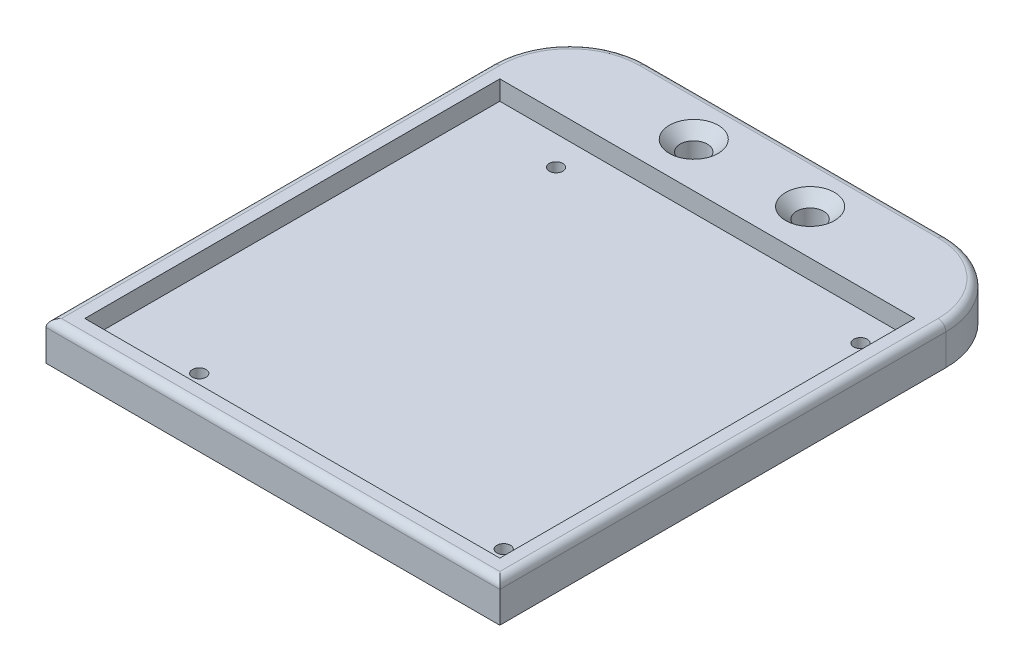
SolidWorks part; units mm, degrees
ref_plane "Front Plane" through (0, 0, 0) normal (0, 0, 1) x (1, 0, 0)
ref_plane "Top Plane" through (0, 0, 0) normal (0, 1, 0) x (1, 0, 0)
ref_plane "Right Plane" through (0, 0, 0) normal (1, 0, 0) x (0, 0, -1)
sketch "Sketch2" plane through (0, 0, 0) normal (0, 1, 0) x (1, 0, 0)
  line L1 (-58.5, 67.5) -> (58.5, 67.5)
  line L2 (-58.5, 67.5) -> (-58.5, -67.5)
  line L3 (-58.5, -67.5) -> (58.5, -67.5)
  line L4 (58.5, 67.5) -> (58.5, -67.5)
  line L5 (-58.5, 67.5) -> (58.5, -67.5) construction
  line L6 (-58.5, -67.5) -> (58.5, 67.5) construction
  point P0 (0, 0)
  dimension "D1" = 117
  dimension "D2" = 135
extrude "Boss-Extrude1" add sketch "Sketch2" along normal blind 10
sketch "Sketch4" plane through (0, 10, 0) normal (0, 1, 0) x (1, 0, 0)
  line L1 (-53.5, 44.5) -> (53.5, 44.5)
  line L2 (-53.5, 44.5) -> (-53.5, -62.5)
  line L3 (-53.5, -62.5) -> (53.5, -62.5)
  line L4 (53.5, 44.5) -> (53.5, -62.5)
  line L5 (-53.5, 44.5) -> (53.5, -62.5) construction
  line L6 (-53.5, -62.5) -> (53.5, 44.5) construction
  point P0 (0, -9)
  point P5 (0, 0)
  dimension "D1" = 107
  dimension "D2" = 107
  dimension "D3" = 5
extrude "Cut-Extrude1" cut sketch "Sketch4" against normal blind 5
sketch "Sketch3" plane through (0, 5, 0) normal (0, 1, 0) x (1, 0, 0)
  line L0 (53.5, -62.5) -> (53.5, 44.5) construction
  line L1 (-31.5, 37) -> (47, 37) construction
  line L2 (-31.5, 37) -> (-31.5, -55) construction
  line L3 (-31.5, -55) -> (47, -55) construction
  line L4 (47, 37) -> (47, -55) construction
  line L5 (-31.5, 37) -> (47, -55) construction
  line L6 (-31.5, -55) -> (47, 37) construction
  line L7 (53.5, 44.5) -> (-53.5, 44.5) construction
  circle A0 centre (-31.5, 37) radius 1.75
  circle A1 centre (47, 37) radius 1.75
  circle A2 centre (47, -55) radius 1.75
  circle A3 centre (-31.5, -55) radius 1.75
  point P0 (7.75, -9)
  point P9 (6.6065, -5.6847)
  dimension "D3" = 3.5
  dimension "D4" = 3.5
  dimension "D5" = 3.5
  dimension "D6" = 3.5
  dimension "D1" = 78.5
  dimension "D2" = 92
  dimension "D7" = 6.5
  dimension "D8" = 7.5
extrude "Cut-Extrude2" cut sketch "Sketch3" against normal through all
sketch "Sketch5" plane through (0, 10, 0) normal (0, 1, 0) x (1, 0, 0)
  line L0 (15, 56) -> (-15, 56) construction
  line L1 (53.5, 44.5) -> (-53.5, 44.5) construction
  point P2 (0, 56)
  dimension "D1" = 30
  dimension "D2" = 11.5
hole_wizard "CSK for M6 Flat Head Machine Screw1" positions "Sketch6" profile "Sketch7" countersink size "M6" standard "ANSI Metric" end condition through all
sketch "Sketch6" plane through (0, 10, 0) normal (0, 1, 0) x (1, 0, 0)
  point P0 (-15, 56)
  point P3 (15, 56)
sketch "Sketch7" plane through (-15, 10, -56) normal (1, 0, 0) x (0, 0, 1)
  line L0 (0, 0) -> (0, 10)
  line L1 (0, 10) -> (3.5, 10)
  line L2 (3.5, 10) -> (3.5, 2.8)
  line L3 (3.5, 2.8) -> (6.3, 0)
  line L5 (6.3, 0) -> (0, 0)
  line L6 (-3.5, 2.8) -> (-6.3, 0) construction
  line L11 (0, -6.35) -> (0, 107.95) construction
  dimension "Thru Hole Dia." = 7
  dimension "Thru Hole Depth" = 10
  dimension "Near C'Sink Dia." = 12.6
  dimension "Near C'Sink Angle" = 90
fillet "Fillet1" radius 20 2 edges at (58.5, 5, -67.5) (-58.5, 5, -67.5)
fillet "Fillet2" radius 2 6 edges at (58.5, 10, 10) (52.6421, 10, -61.6421) (0, 10, -67.5) (-52.6421, 10, -61.6421) (0, 10, 67.5) (-58.5, 10, 10)
